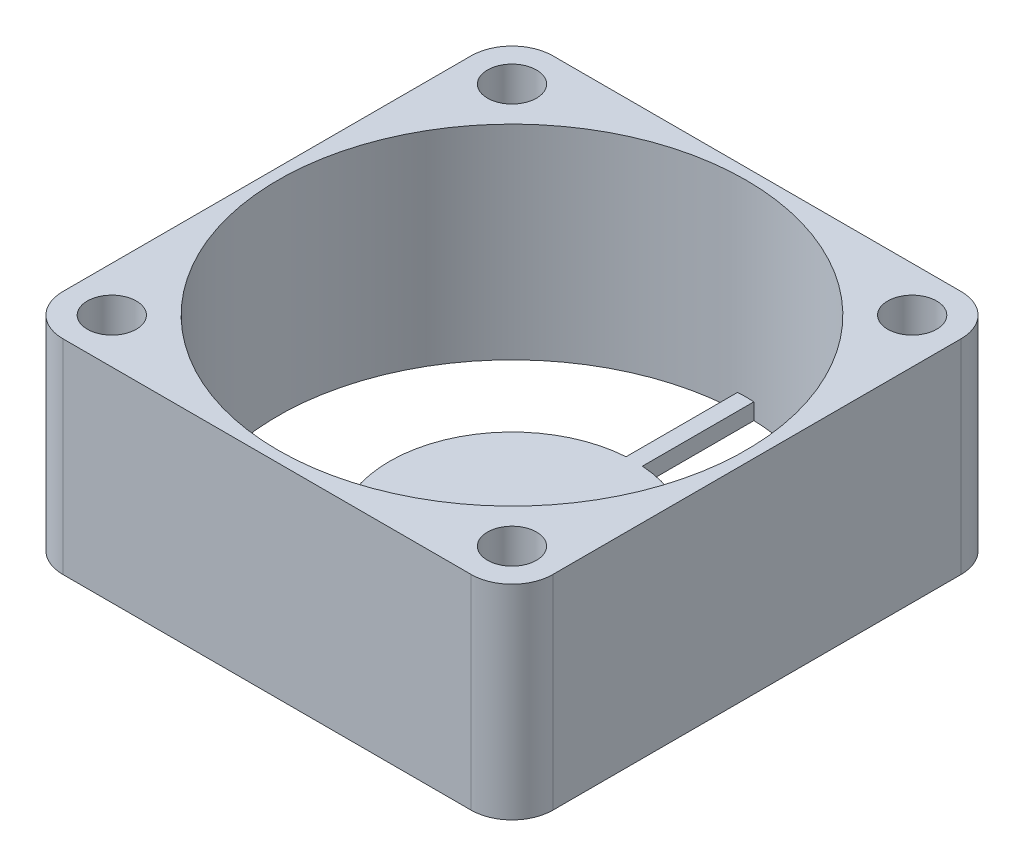
SolidWorks part; units mm, degrees
material "ABS PC"
ref_plane "Front Plane" through (0, 0, 0) normal (0, 0, 1) x (1, 0, 0)
ref_plane "Top Plane" through (0, 0, 0) normal (0, 1, 0) x (1, 0, 0)
ref_plane "Right Plane" through (0, 0, 0) normal (1, 0, 0) x (0, 0, -1)
sketch "Sketch5" plane through (0, 0, 0) normal (0, 1, 0) x (1, 0, 0)
  line L0 (7.3787, 15) -> (15, 7.3787) construction
  line L1 (-15, 15) -> (15, 15)
  line L2 (-15, 15) -> (-15, -15)
  line L3 (-15, -15) -> (15, -15)
  line L4 (15, 15) -> (15, -15)
  line L5 (-15, 15) -> (15, -15) construction
  line L6 (-15, -15) -> (15, 15) construction
  line L8 (5.2574, 15) -> (15, 5.2574) construction
  circle A0 centre (12.25, 12.25) radius 1.5
  circle A1 centre (12.25, -12.25) radius 1.5
  circle A2 centre (-12.25, 12.25) radius 1.5
  circle A3 centre (-12.25, -12.25) radius 1.5
  circle A4 centre (0, 0) radius 7.5
  circle A5 centre (0, 0) radius 14.3241
  point P0 (0, 0)
  point P21 (11.1893, 11.1893)
  dimension "D3" = 3
  dimension "D4" = 15
  dimension "D1" = 30
  dimension "D2" = 24.5
  dimension "D5" = 1.5
extrude "Boss-Extrude1" add sketch "Sketch5" along normal blind 12.5 contours L4 L1 L2 L3 A5 A3 A2 A1 A0
fillet "Fillet1" radius 2.5 4 edges at (-15, 6.25, -15) (15, 6.25, -15) (-15, 6.25, 15) (15, 6.25, 15)
sketch "Sketch6" plane through (0, 0, 0) normal (0, 1, 0) x (1, 0, 0)
  line L0 (0.5, 7.4833) -> (0.5, 14.3154)
  line L1 (-0.5, 7.4833) -> (-0.5, 14.3154)
  line L2 (0, 0) -> (0, 14.3241) construction
  line L3 (6.2307, -4.1747) -> (12.1475, -7.5907)
  line L4 (15, 15) -> (-15, 15)
  line L5 (15, -15) -> (15, 15)
  line L6 (-15, -15) -> (15, -15)
  line L7 (-15, 15) -> (-15, -15)
  line L8 (15, 15) -> (-15, 15)
  line L9 (15, -15) -> (15, 15)
  line L10 (-15, -15) -> (15, -15)
  line L11 (-15, 15) -> (-15, -15)
  line L12 (6.7307, -3.3086) -> (12.6475, -6.7247)
  line L13 (-6.7307, -3.3086) -> (-12.6475, -6.7247)
  line L14 (-6.2307, -4.1747) -> (-12.1475, -7.5907)
  arc A0 (0.5, 14.3154) -> (-0.5, 14.3154) centre (0, 0) ccw
  circle A1 centre (0, 0) radius 14.3241
  circle A2 centre (0, 0) radius 14.3241
  circle A3 centre (-12.25, -12.25) radius 1.5
  circle A4 centre (-12.25, -12.25) radius 1.5
  circle A5 centre (-12.25, 12.25) radius 1.5
  circle A6 centre (-12.25, 12.25) radius 1.5
  circle A7 centre (12.25, -12.25) radius 1.5
  circle A8 centre (12.25, -12.25) radius 1.5
  circle A9 centre (12.25, 12.25) radius 1.5
  circle A10 centre (12.25, 12.25) radius 1.5
  circle A11 centre (0, 0) radius 7.5
  circle A12 centre (0, 0) radius 7.5
  arc A13 (12.1475, -7.5907) -> (12.6475, -6.7247) centre (0, 0) ccw
  arc A14 (-12.6475, -6.7247) -> (-12.1475, -7.5907) centre (0, 0) ccw
  point P39 (0, 0)
  dimension "D8" = 1
  dimension "D1" = 0
  dimension "D2" = 0
  dimension "D3" = 0
  dimension "D4" = 0
  dimension "D5" = 0
  dimension "D6" = 0
  dimension "D7" = 0
  dimension "D9" = 3
extrude "Boss-Extrude2" add sketch "Sketch6" along normal offset from surface (1 mm away) 1 separate body contours A12 | A12 L2 A2 L1 | L2 A12 L0 A0 | A12 L3 A2 L12 | A12 L13 A2 L14 up to face at (0, 0, 14.3241)
